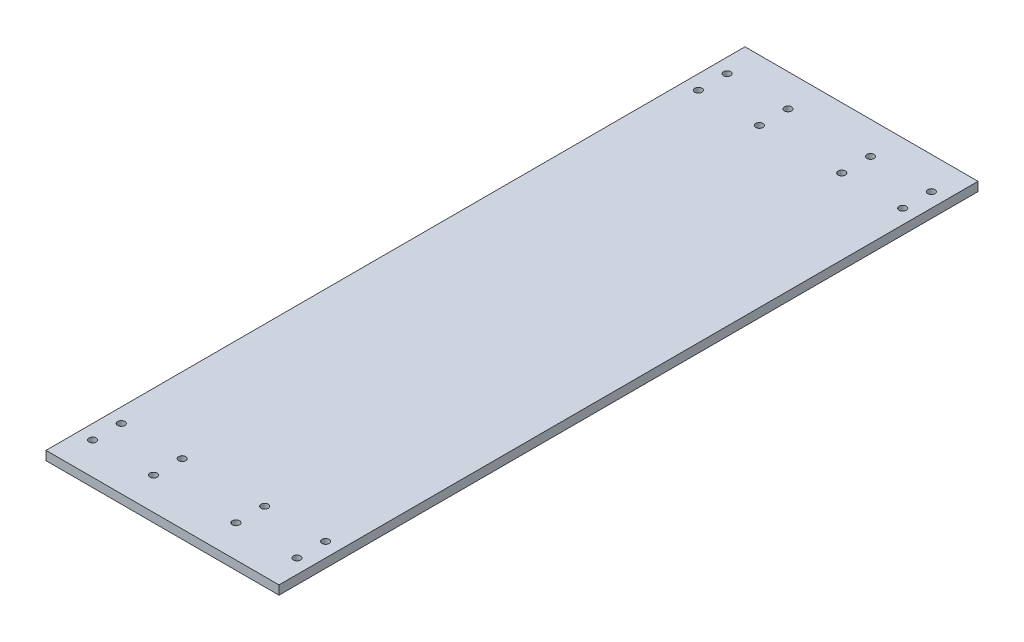
SolidWorks part; units mm, degrees
ref_plane "Front Plane" through (0, 0, 0) normal (0, 0, 1) x (1, 0, 0)
ref_plane "Top Plane" through (0, 0, 0) normal (0, 1, 0) x (1, 0, 0)
ref_plane "Right Plane" through (0, 0, 0) normal (1, 0, 0) x (0, 0, -1)
sketch "Sketch2" plane through (0, 0, 0) normal (0, 1, 0) x (1, 0, 0)
  line L1 (-65, -195) -> (65, -195)
  line L2 (-65, -195) -> (-65, 195)
  line L3 (-65, 195) -> (65, 195)
  line L4 (65, -195) -> (65, 195)
  line L5 (-65, -195) -> (65, 195) construction
  line L6 (-65, 195) -> (65, -195) construction
  point P0 (0, 0)
  dimension "D1" = 390
  dimension "D2" = 130
extrude "Boss-Extrude1" add sketch "Sketch2" along normal blind 5
sketch "Sketch3" plane through (0, 5, 0) normal (0, 1, 0) x (1, 0, 0)
  line L0 (-65, 195) -> (-65, -195) construction
  line L1 (65, 195) -> (-65, 195) construction
  circle A0 centre (-57, 177) radius 2
  circle A1 centre (-57, 161) radius 2
  circle A2 centre (-23, 177) radius 2
  circle A3 centre (-23, 161) radius 2
  dimension "D1" = 4
  dimension "D2" = 4
  dimension "D3" = 4
  dimension "D4" = 4
  dimension "D5" = 8
  dimension "D6" = 34
  dimension "D7" = 18
  dimension "D8" = 16
extrude "Cut-Extrude1" cut sketch "Sketch3" against normal blind 10
mirror "Mirror1" about plane through (0, 0, 0) normal (0, 0, 1) of "Cut-Extrude1" second plane through (0, 0, 0) second plane normal (1, 0, 0)
